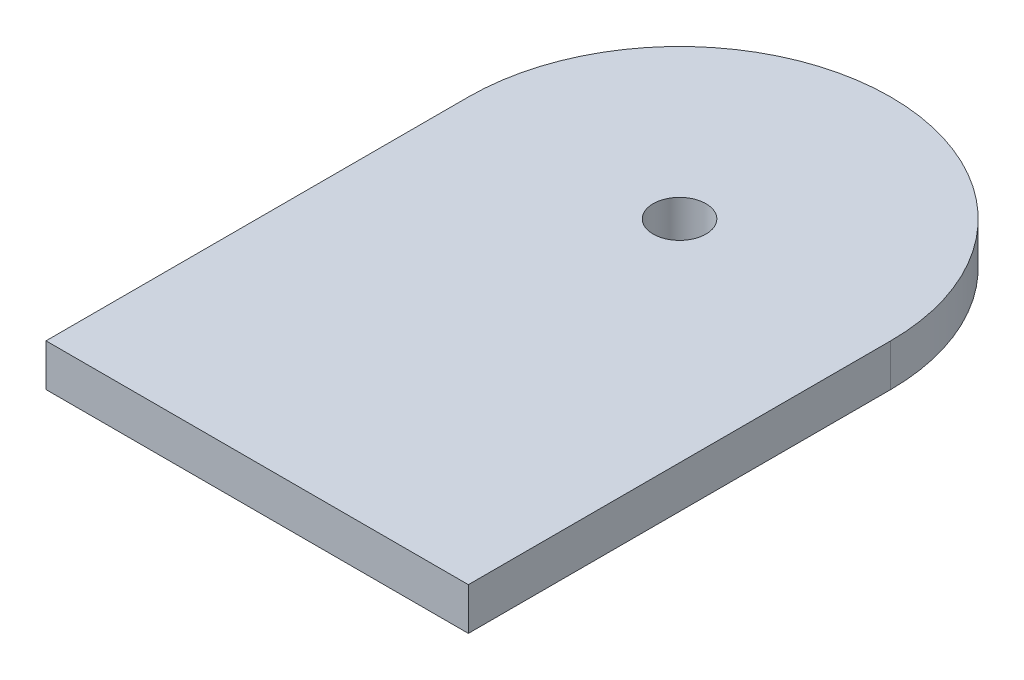
SolidWorks part; units mm, degrees
ref_plane "Front Plane" through (0, 0, 0) normal (0, 0, 1) x (1, 0, 0)
ref_plane "Top Plane" through (0, 0, 0) normal (0, 1, 0) x (1, 0, 0)
ref_plane "Right Plane" through (0, 0, 0) normal (1, 0, 0) x (0, 0, -1)
sketch "Sketch1" plane through (0, 0, 0) normal (0, 1, 0) x (1, 0, 0)
  line L1 (0, 0) -> (80, 0)
  line L2 (0, 0) -> (0, 80)
  line L4 (80, 0) -> (80, 80)
  arc A0 (80, 80) -> (0, 80) centre (40, 80) ccw
  circle A1 centre (40, 80) radius 5
  dimension "D1" = 40
  dimension "D2" = 10
  dimension "D3" = 80
extrude "Boss-Extrude1" add sketch "Sketch1" along normal blind 8
